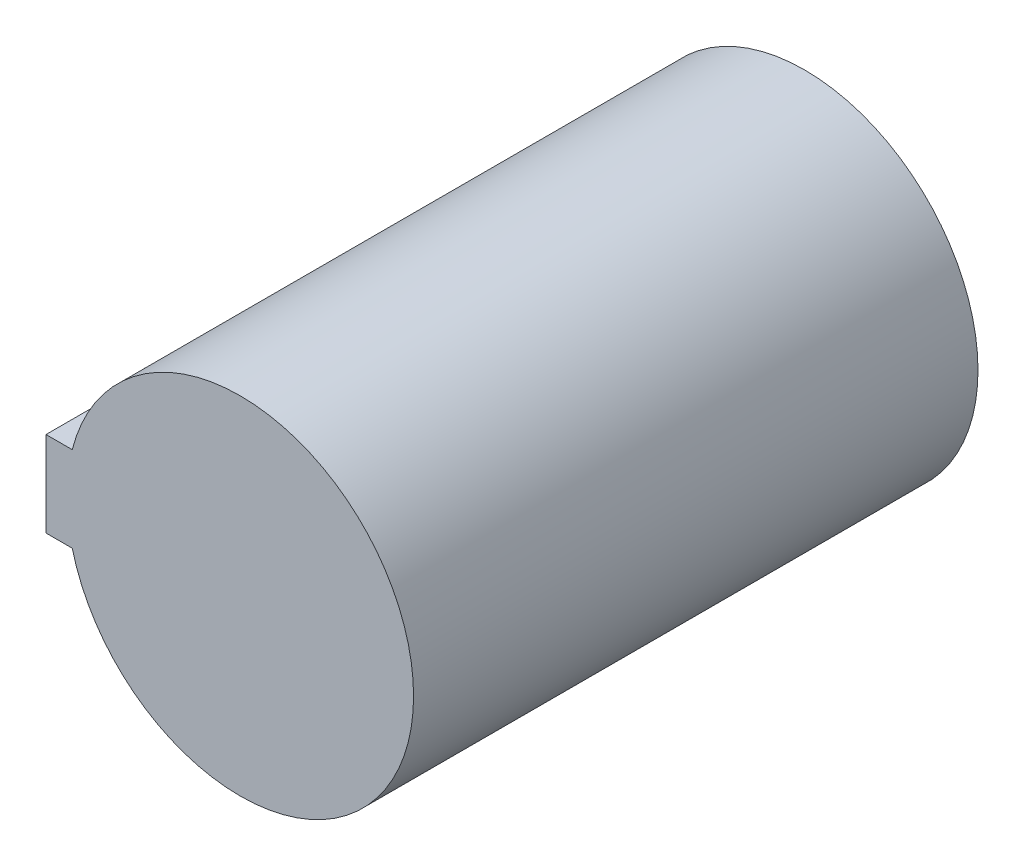
SolidWorks part; units mm, degrees
ref_plane "Front Plane" through (0, 0, 0) normal (1, 0, 0) x (0, 1, 0)
ref_plane "Top Plane" through (0, 0, 0) normal (0, 0, 1) x (0, 1, 0)
ref_plane "Right Plane" through (0, 0, 0) normal (0, 1, 0) x (-1, 0, 0)
sketch "Sketch1" plane through (0, 0, 0) normal (0, 0, 1) x (0, 1, 0)
  line L1 (-4.9, 22.3) -> (4.9, 22.3)
  line L2 (-4.9, 22.3) -> (-4.9, 19.2873)
  line L4 (4.9, 22.3) -> (4.9, 19.2873)
  arc A0 (-4.9, 19.2873) -> (4.9, 19.2873) centre (0, 0) ccw
  point P3 (0, 19.9)
  dimension "D1" = 39.8
  dimension "D2" = 9.8
extrude "Boss-Extrude1" add sketch "Sketch1" along normal blind 25
sketch "Sketch2" plane through (0, 0, 0) normal (0, 0, -1) x (1, 0, 0)
  circle A0 centre (0, 0) radius 19.9
  dimension "D1" = 39.8
extrude "Boss-Extrude3" add sketch "Sketch2" along normal blind 39.8
